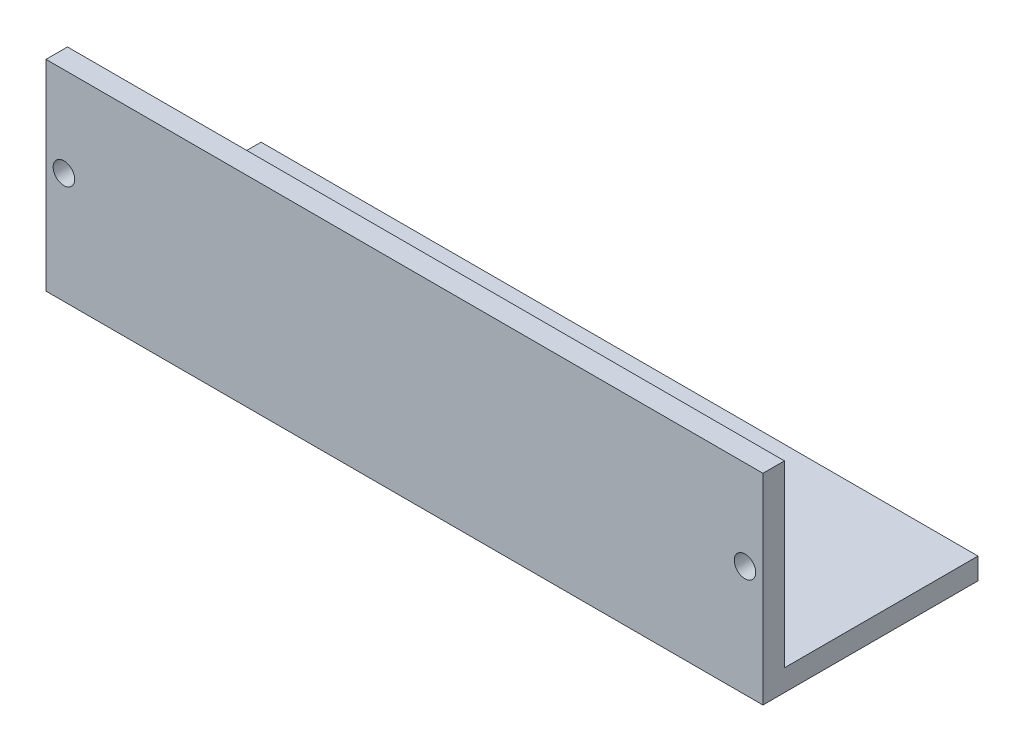
SolidWorks part; units mm, degrees
ref_plane "Front Plane" through (0, 0, 0) normal (0, 0, 1) x (1, 0, 0)
ref_plane "Top Plane" through (0, 0, 0) normal (0, 1, 0) x (1, 0, 0)
ref_plane "Right Plane" through (0, 0, 0) normal (1, 0, 0) x (0, 0, -1)
sketch "Sketch1" plane through (0, 0, 0) normal (0, 0, 1) x (1, 0, 0)
  line L0 (-47.5, 0) -> (47.5, 0) construction
  line L1 (-50, 12.5) -> (50, 12.5)
  line L2 (-50, 12.5) -> (-50, -12.5)
  line L3 (-50, -12.5) -> (50, -12.5)
  line L4 (50, 12.5) -> (50, -12.5)
  line L5 (-50, 12.5) -> (50, -12.5) construction
  line L6 (-50, -12.5) -> (50, 12.5) construction
  circle A0 centre (-47.5, 0) radius 1.5
  circle A1 centre (47.5, 0) radius 1.5
  point P0 (0, 0)
  point P9 (0, 0)
  dimension "D2" = 3
  dimension "D1" = 100
  dimension "D3" = 95
  dimension "D4" = 25
extrude "Boss-Extrude1" add sketch "Sketch1" along normal blind 3
sketch "Sketch2" plane through (0, -12.5, 0) normal (0, -1, 0) x (1, 0, 0)
  line L0 (50, 3) -> (50, 0) construction
  line L1 (-50, 3) -> (50, 3)
  line L2 (-50, 3) -> (-50, -27)
  line L3 (-50, -27) -> (50, -27)
  line L4 (50, 3) -> (50, -27)
  dimension "D1" = 30
extrude "Boss-Extrude2" add sketch "Sketch2" along normal blind 3
sketch "Sketch3" plane through (0, 0, 0) normal (1, 0, 0) x (0, 0, -1)
  line L0 (0, 12.5) -> (10, -12.5)
  line L1 (27, -12.5) -> (0, -12.5) construction
  line L2 (0, -12.5) -> (0, 12.5) construction
  dimension "D1" = 10
rib "Rib1" sketch "Sketch3" sketch "Sketch3" thickness 40 extrusion direction parallel to sketch draft on no parameters "D1"=40
